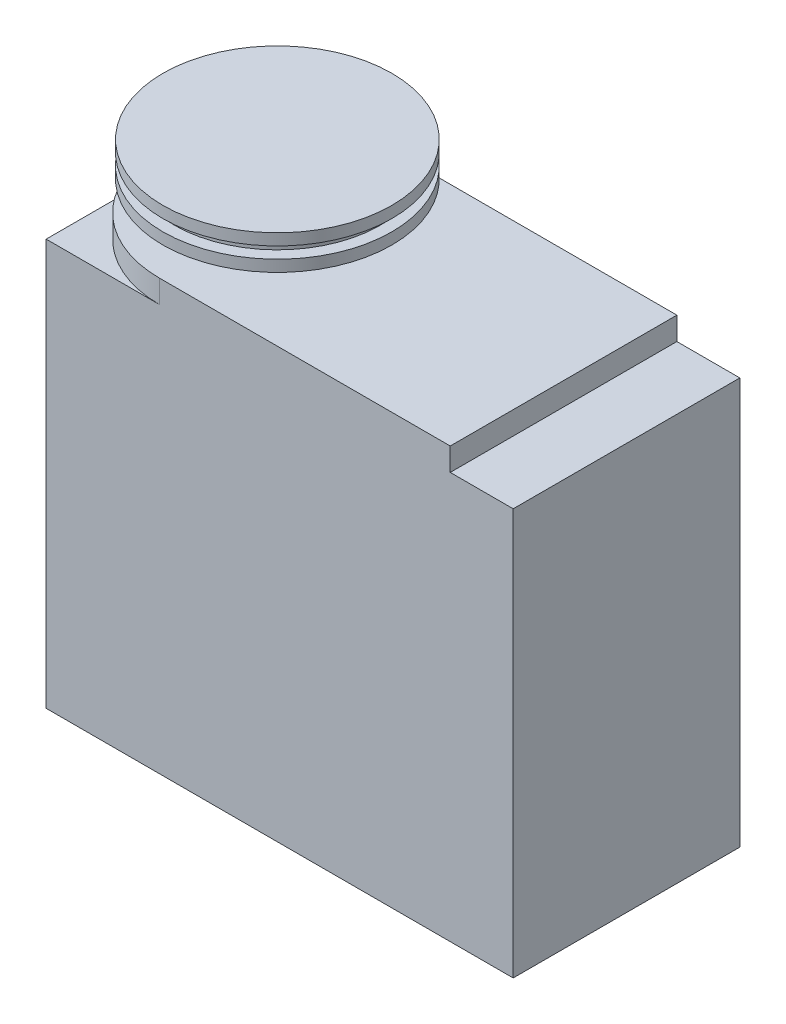
SolidWorks part; units mm, degrees
ref_plane "Front Plane" through (0, 0, 0) normal (0, 0, 1) x (1, 0, 0)
ref_plane "Top Plane" through (0, 0, 0) normal (0, 1, 0) x (1, 0, 0)
ref_plane "Right Plane" through (0, 0, 0) normal (1, 0, 0) x (0, 0, -1)
sketch "Sketch1" plane through (0, 0, 0) normal (0, 1, 0) x (1, 0, 0)
  line L1 (-20.4, -9.9) -> (20.4, -9.9)
  line L2 (-20.4, -9.9) -> (-20.4, 9.9)
  line L3 (-20.4, 9.9) -> (20.4, 9.9)
  line L4 (20.4, -9.9) -> (20.4, 9.9)
  line L5 (-20.4, -9.9) -> (20.4, 9.9) construction
  line L6 (-20.4, 9.9) -> (20.4, -9.9) construction
  point P0 (0, 0)
  dimension "D1" = 19.8
  dimension "D2" = 40.8
extrude "Boss-Extrude1" add sketch "Sketch1" along normal blind 35.5
sketch "Sketch2" plane through (0, 0, 0) normal (0, -1, 0) x (1, 0, 0)
  line L0 (-20.4, -9.9) -> (-20.4, 9.9) construction
  line L1 (-20.4, 9.9) -> (20.4, 9.9) construction
  circle A0 centre (-10.1, 0) radius 6
  dimension "D1" = 10.3
  dimension "D3" = 12
  dimension "D2" = 9.9
sketch "Sketch4" plane through (0, 35.5, 0) normal (0, 1, 0) x (1, 0, 0)
  line L0 (14.9, 9.9) -> (14.9, -9.9)
  line L1 (20.4, 9.9) -> (-20.4, 9.9) construction
  line L2 (-20.4, -9.9) -> (20.4, -9.9) construction
  line L3 (14.9, 9.9) -> (-10.5, 9.9)
  line L4 (-10.5, -9.9) -> (14.9, -9.9)
  line L5 (-20.4, 9.9) -> (-20.4, -9.9) construction
  line L6 (20.4, -9.9) -> (20.4, 9.9) construction
  arc A0 (-10.5, 9.9) -> (-10.5, -9.9) centre (-10.5, 0) ccw
  point P9 (-20.4, 0)
  point P12 (14.9, 0)
  dimension "D1" = 5.5
extrude "Boss-Extrude2" add sketch "Sketch4" along normal blind 2
extrude "Boss-Extrude3" add sketch "Sketch2" along normal blind 1.7521 separate body
sketch "Sketch5" plane through (0, 37.5, 0) normal (0, 1, 0) x (1, 0, 0)
  circle A0 centre (-10.1, 0) radius 6
  dimension "D1" = 12
  dimension "D2" = 10.3
extrude "Boss-Extrude4" add sketch "Sketch5" along normal blind 1.75
sketch "Sketch6" plane through (0, -1.7521, 0) normal (0, -1, 0) x (1, 0, 0)
  circle A0 centre (-10.1, 0) radius 2.5
  dimension "D1" = 5
extrude "Boss-Extrude5" add sketch "Sketch6" along normal blind 3.5
sketch "Sketch7" plane through (0, 39.25, 0) normal (0, 1, 0) x (1, 0, 0)
  circle A0 centre (-10.1, 0) radius 2.75
  dimension "D1" = 5.5
extrude "Boss-Extrude6" add sketch "Sketch7" along normal blind 1
sketch "Sketch8" plane through (-20.4, 0, 0) normal (-1, 0, 0) x (0, 0, 1)
  line L0 (-9.9, 0) -> (9.9, 0) construction
  line L1 (-3.5, 3) -> (3.5, 3)
  line L2 (-3.5, 3) -> (-3.5, 7)
  line L3 (-3.5, 7) -> (3.5, 7)
  line L4 (3.5, 3) -> (3.5, 7)
  line L5 (-3.5, 3) -> (3.5, 7) construction
  line L6 (-3.5, 7) -> (3.5, 3) construction
  point P0 (0, 5)
  dimension "D1" = 4
  dimension "D2" = 7
  dimension "D3" = 3
extrude "Boss-Extrude7" add sketch "Sketch8" along normal blind 5
sketch "Sketch10" plane through (0, 40.25, 0) normal (0, 1, 0) x (1, 0, 0)
  circle A0 centre (-10.1, 0) radius 10
  point P3 (-10.1, -10)
  dimension "D1" = 20
extrude "Boss-Extrude9" add sketch "Sketch10" along normal blind 1
sketch "Sketch14" plane through (0, 41.25, 0) normal (0, 1, 0) x (1, 0, 0)
  circle A0 centre (-10.1, 0) radius 9
  dimension "D1" = 18
extrude "Boss-Extrude10" add sketch "Sketch14" along normal blind 1
sketch "Sketch15" plane through (0, 42.25, 0) normal (0, 1, 0) x (1, 0, 0)
  circle A0 centre (-10.1, 0) radius 10
  dimension "D1" = 20
extrude "Boss-Extrude11" add sketch "Sketch15" along normal blind 1
